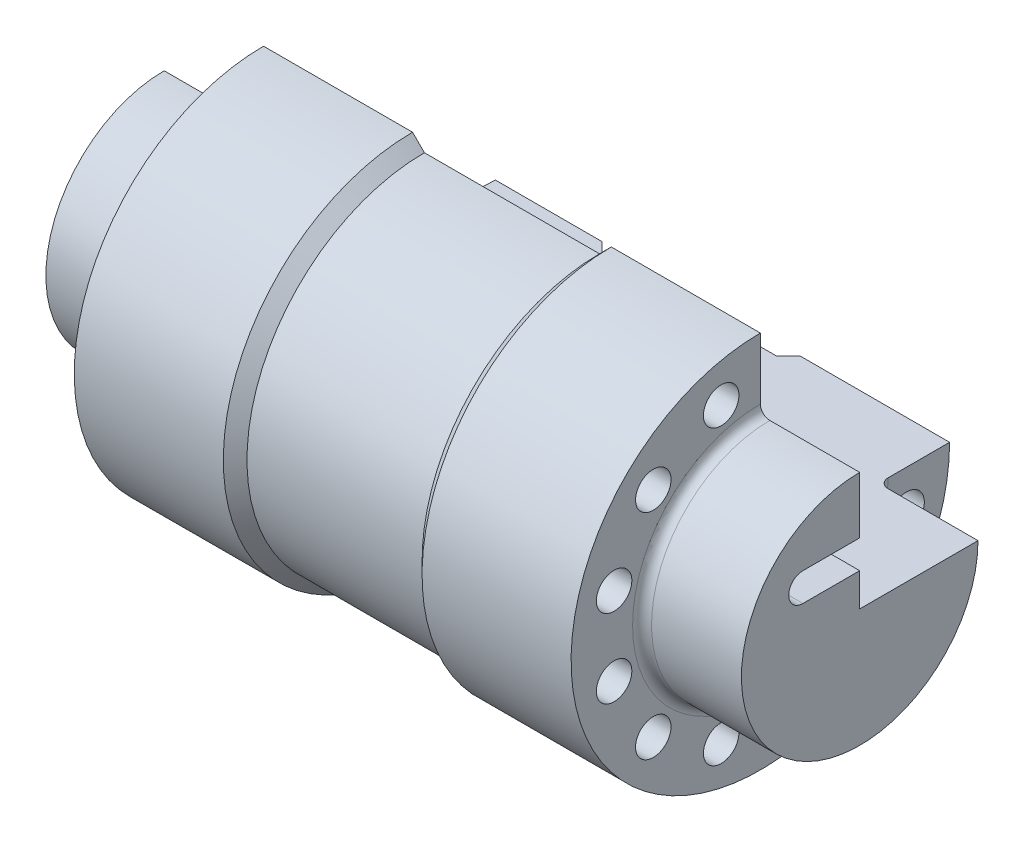
SolidWorks part; units mm, degrees
material "AISI 1020"
ref_plane "Plan de face" through (0, 0, 0) normal (0, 0, 1) x (1, 0, 0)
ref_plane "Plan de dessus" through (0, 0, 0) normal (0, 1, 0) x (1, 0, 0)
ref_plane "Plan de droite" through (0, 0, 0) normal (1, 0, 0) x (0, 0, -1)
sketch "Esquisse1" plane through (0, 0, 0) normal (0, 0, 1) x (1, 0, 0)
  line L0 (0, 0) -> (147, 0) construction
  line L1 (0, 0) -> (0, 25)
  line L2 (0, 25) -> (21, 25)
  line L3 (21, 25) -> (21, 40)
  line L4 (21, 40) -> (52.5, 40)
  line L5 (52.5, 40) -> (55, 37.5)
  line L6 (55, 37.5) -> (92, 37.5)
  line L7 (92, 37.5) -> (94.5, 40)
  line L8 (94.5, 40) -> (126, 40)
  line L9 (126, 40) -> (126, 25)
  line L10 (126, 25) -> (147, 25)
  line L11 (147, 25) -> (147, 0)
  line L12 (0, 0) -> (147, 0)
  dimension "D1" = 147
  dimension "D2" = 21
  dimension "D3" = 31.5
  dimension "D4" = 31.5
  dimension "D5" = 21
  dimension "D6" = 50
  dimension "D7" = 50
  dimension "D8" = 80
  dimension "D9" = 80
  dimension "D10" = 2.5
  dimension "D11" = 45
revolve "Révolution1" add sketch "Esquisse1" angle 360 about L0
fillet "Congé1" radius 2 2 edges at (126, 0, 25) (21, 0, 25)
sketch "Esquisse3" plane through (147, 0, 0) normal (1, 0, 0) x (0, 0, -1)
  line L0 (0, 0) -> (0, 40)
  line L1 (0, 0) -> (40, 0)
  circle A0 centre (0, 0) radius 40 construction
  arc A1 (40, 0) -> (0, 40) centre (0, 0) ccw
extrude "Enlèv. mat.-Extru.1" cut sketch "Esquisse3" against normal through all
sketch "Esquisse4" plane through (147, 0, 0) normal (1, 0, 0) x (0, 0, -1)
  line L0 (12, 10) -> (-12, 10) construction
  line L1 (0, 25) -> (0, 0) construction
  line L2 (12, 7) -> (-12, 7)
  line L3 (12, 13) -> (-12, 13)
  arc A0 (12, 7) -> (12, 13) centre (12, 10) ccw
  arc A1 (-12, 13) -> (-12, 7) centre (-12, 10) ccw
  point P4 (0, 10)
  dimension "D2" = 3
  dimension "D1" = 12
  dimension "D3" = 7
extrude "Enlèv. mat.-Extru.2" cut sketch "Esquisse4" against normal through all
sketch "Esquisse6" plane through (126, 0, 0) normal (1, 0, 0) x (0, 0, -1)
  line L1 (0, 0) -> (-8.2822, 30.9096) construction
  line L2 (0, 27) -> (0, 40) construction
  circle A1 centre (0, 0) radius 32 construction
  circle A2 centre (-8.2822, 30.9096) radius 3.75
  dimension "D1" = 64
  dimension "D2" = 15
  dimension "D3" = 7.5
extrude "Enlèv. mat.-Extru.4" cut sketch "Esquisse6" against normal through all
pattern_circular "Répétition circulaire1" count 9 every 30 about axis through (0, 0, 0) along (1, 0, 0) of "Enlèv. mat.-Extru.4"
sketch "Esquisse7" plane through (0, 0, 0) normal (0, 1, 0) x (1, 0, 0)
  line L0 (30, 40) -> (0, 40)
  line L1 (21, 40) -> (52.5, 40) construction
  line L2 (0, 0) -> (0, 25) construction
  line L3 (27.1892, 27.3215) -> (31.7208, 25.2084)
  line L4 (5.2094, 10.4558) -> (6.0777, 5.5317)
  line L5 (0, 40) -> (0, 10)
  arc A0 (30, 40) -> (27.1892, 27.3215) centre (0, 40) cw
  arc A1 (31.7208, 25.2084) -> (6.0777, 5.5317) centre (0, 40) cw
  arc A2 (5.2094, 10.4558) -> (0, 10) centre (0, 40) cw
  dimension "D1" = 30
  dimension "D2" = 35
  dimension "D3" = 25
  dimension "D4" = 10
extrude "Enlèv. mat.-Extru.5" cut sketch "Esquisse7" against normal blind 80
equation "\"A\"= 147"
equation "\"B\"= 21"
equation "\"C\"= 31.50"
equation "\"D1@Esquisse1\"=\"A\""
equation "\"D2@Esquisse1\"=\"B\""
equation "\"D3@Esquisse1\"=\"C\""
equation "\"D4@Esquisse1\"=\"C\""
equation "\"D5@Esquisse1\"=\"B\""
